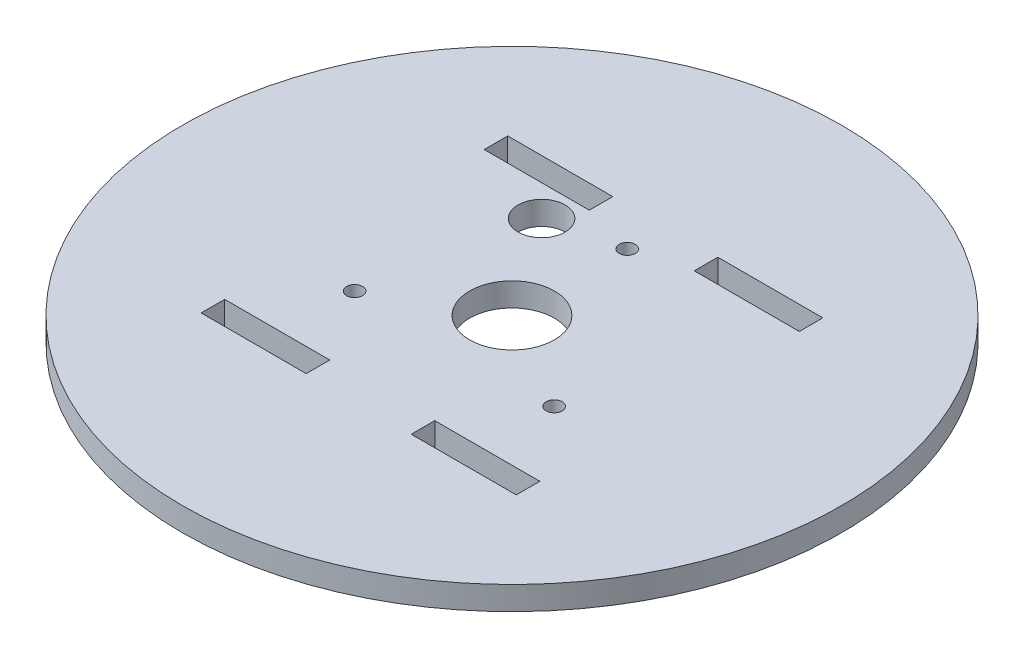
SolidWorks part; units mm, degrees
ref_plane "Front Plane" through (0, 0, 0) normal (0, 0, 1) x (1, 0, 0)
ref_plane "Top Plane" through (0, 0, 0) normal (0, 1, 0) x (1, 0, 0)
ref_plane "Right Plane" through (0, 0, 0) normal (1, 0, 0) x (0, 0, -1)
sketch "Sketch1" plane through (0, 0, 0) normal (0, 1, 0) x (1, 0, 0)
  line L0 (0, 28.93) -> (0, 11.43) construction
  line L1 (0, 0) -> (-25.0541, -14.465) construction
  line L2 (0, 0) -> (25.0541, -14.465) construction
  line L3 (26.9239, -15.5445) -> (25.0541, -14.465) construction
  line L4 (-26.9239, -15.5445) -> (-25.0541, -14.465) construction
  line L5 (0, 0) -> (-18.6481, 26.6323) construction
  circle A0 centre (0, 0) radius 88.9
  circle A1 centre (0, 0) radius 11.43
  circle A2 centre (0, 31.089) radius 2.159
  circle A3 centre (26.9239, -15.5445) radius 2.159
  circle A4 centre (-26.9239, -15.5445) radius 2.159
  circle A5 centre (-18.6481, 26.6323) radius 6.35
  dimension "D1" = 177.8
  dimension "D2" = 22.86
  dimension "D3" = 4.318
  dimension "D4" = 17.5
  dimension "D8" = 12.7
  dimension "D9" = 35
  dimension "D6" = 120
  dimension "D7" = 120
  dimension "D10" = 32.512
  dimension "D5" = 3
extrude "Body" add sketch "Sketch1" along normal blind 6.35
sketch "Sketch2" plane through (0, 6.35, 0) normal (0, 1, 0) x (1, 0, 0)
  line L0 (-42.5, 0) -> (42.5, 0) construction
  line L1 (-42.5, 35) -> (42.5, 35) construction
  line L2 (-42.5, 35) -> (-42.5, -35) construction
  line L3 (-42.5, -35) -> (42.5, -35) construction
  line L4 (42.5, 35) -> (42.5, -35) construction
  line L5 (0, 35) -> (0, -35) construction
  line L6 (-42.5, 35) -> (-42.5, 41.35)
  line L7 (-42.5, 41.35) -> (-14.1667, 41.35)
  line L8 (-14.1667, 41.35) -> (-14.1667, 35)
  line L9 (-14.1667, 35) -> (-42.5, 35)
  line L10 (14.1667, 35) -> (14.1667, 41.35)
  line L11 (14.1667, 41.35) -> (42.5, 41.35)
  line L12 (42.5, 41.35) -> (42.5, 35)
  line L13 (42.5, 35) -> (14.1667, 35)
  line L14 (-14.1667, 41.35) -> (14.1667, 41.35) construction
  line L19 (42.5, -35) -> (14.1667, -35)
  line L20 (42.5, -41.35) -> (42.5, -35)
  line L21 (14.1667, -41.35) -> (42.5, -41.35)
  line L22 (14.1667, -35) -> (14.1667, -41.35)
  line L23 (-14.1667, -35) -> (-42.5, -35)
  line L24 (-14.1667, -41.35) -> (-14.1667, -35)
  line L25 (-42.5, -41.35) -> (-14.1667, -41.35)
  line L26 (-42.5, -35) -> (-42.5, -41.35)
  point P10 (0, 0)
  dimension "D1" = 85
  dimension "D2" = 70
  dimension "D3" = 6.35
extrude "Mounting teeth" cut sketch "Sketch2" against normal up to next
